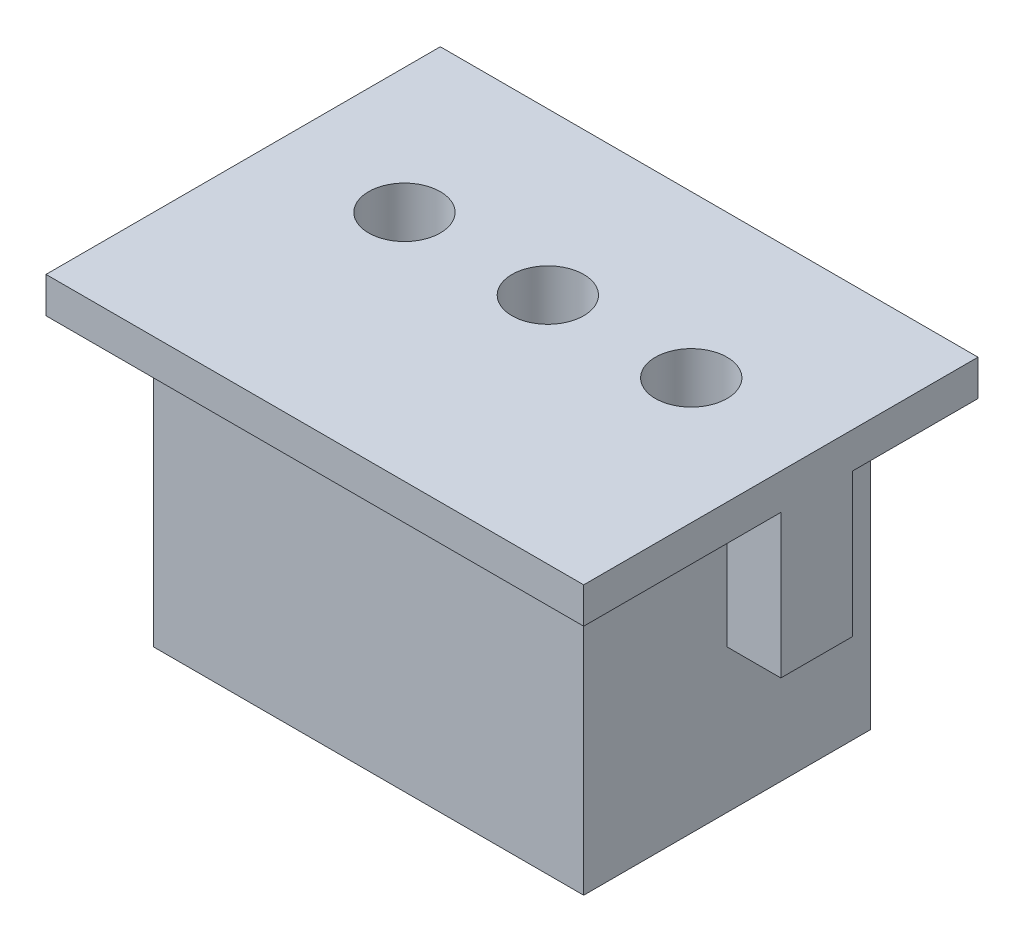
SolidWorks part; units mm, degrees
ref_plane "Front Plane" through (0, 0, 0) normal (0, 0, 1) x (1, 0, 0)
ref_plane "Top Plane" through (0, 0, 0) normal (0, 1, 0) x (1, 0, 0)
ref_plane "Right Plane" through (0, 0, 0) normal (1, 0, 0) x (0, 0, -1)
sketch "Sketch1" plane through (0, 0, 0) normal (0, 1, 0) x (1, 0, 0)
  line L1 (-3, -2) -> (3, -2)
  line L2 (-3, -2) -> (-3, 2)
  line L3 (-3, 2) -> (3, 2)
  line L4 (3, -2) -> (3, 2)
  line L5 (-3, -2) -> (3, 2) construction
  line L6 (-3, 2) -> (3, -2) construction
  point P0 (0, 0)
  dimension "D1" = 6
  dimension "D2" = 4
extrude "Boss-Extrude1" add sketch "Sketch1" along normal blind 4
sketch "Sketch2" plane through (3, 0, 0) normal (1, 0, 0) x (0, 0, -1)
  line L0 (0, 4) -> (0, 2)
  line L1 (-2, 4) -> (2, 4) construction
  line L2 (0, 2) -> (1, 2)
  line L3 (1, 2) -> (1, 4)
  line L4 (1, 4) -> (0, 4)
  line L5 (-2, 4) -> (-2, 0) construction
  dimension "D1" = 2
  dimension "D2" = 1
  dimension "D3" = 2
extrude "Boss-Extrude2" add sketch "Sketch2" along normal blind 0.75
mirror "Mirror1" about plane through (0, 0, 0) normal (1, 0, 0) of "Boss-Extrude2"
sketch "Sketch3" plane through (0, 4, 0) normal (0, 1, 0) x (1, 0, 0)
  line L15 (3, 2) -> (-3, 2) construction
  line L16 (-3.75, -2.75) -> (3.75, -2.75)
  line L17 (-3.75, -2.75) -> (-3.75, 2.75)
  line L18 (-3.75, 2.75) -> (3.75, 2.75)
  line L19 (3.75, -2.75) -> (3.75, 2.75)
  line L20 (-3.75, -2.75) -> (3.75, 2.75) construction
  line L21 (-3.75, 2.75) -> (3.75, -2.75) construction
  line L22 (-3, 2) -> (-3, 1) construction
  point P3 (0, 0)
  dimension "D1" = 0.75
  dimension "D2" = 0.75
extrude "Boss-Extrude3" add sketch "Sketch3" along normal blind 0.5
sketch "Sketch4" plane through (0, 0, 0) normal (0, -1, 0) x (1, 0, 0)
  line L0 (-3, 0) -> (-3, -1) construction
  circle A0 centre (-2, -0.5) radius 0.5
  circle A1 centre (0, -0.5) radius 0.5
  circle A2 centre (2, -0.5) radius 0.5
  point P9 (-3, -0.5)
  dimension "D3" = 1
  dimension "D1" = 2
  dimension "D2" = 2
extrude "Cut-Extrude1" cut sketch "Sketch4" against normal through all
